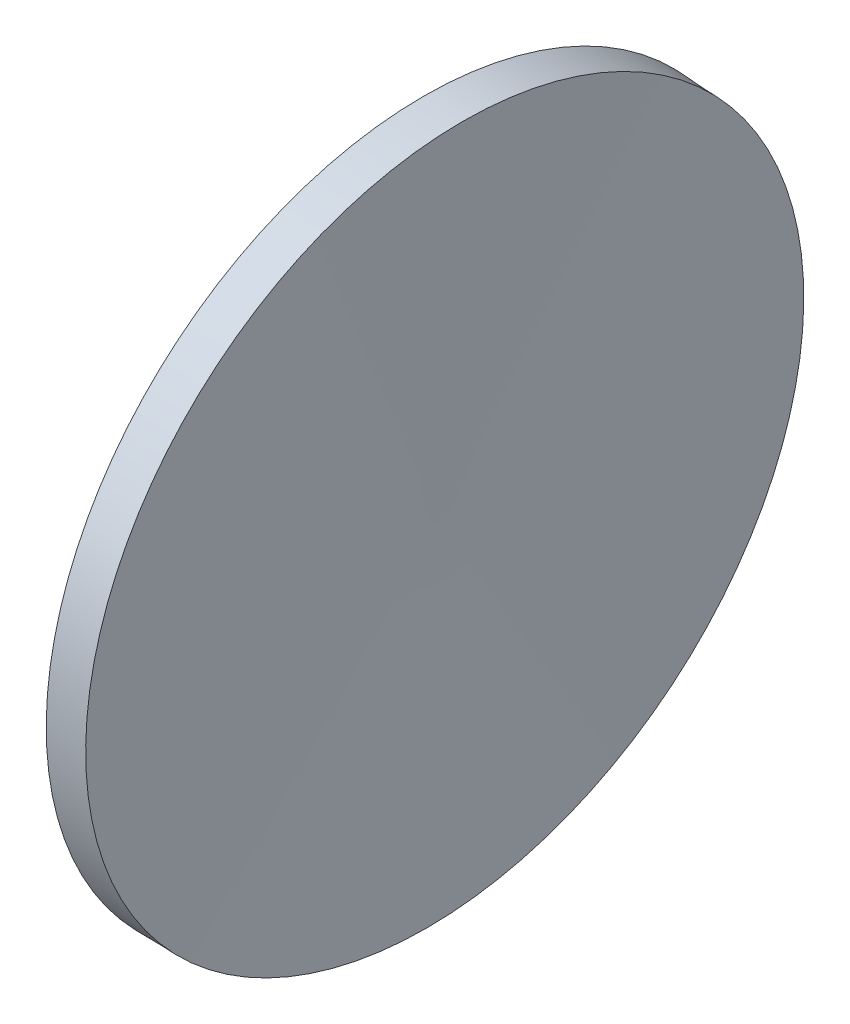
SolidWorks part; units mm, degrees
material "玻璃"
ref_plane "前视基准面" through (0, 0, 0) normal (0, 0, 1) x (1, 0, 0)
ref_plane "上视基准面" through (0, 0, 0) normal (0, 1, 0) x (1, 0, 0)
ref_plane "右视基准面" through (0, 0, 0) normal (1, 0, 0) x (0, 0, -1)
sketch "草图1" plane through (0, 0, 0) normal (0, 0, 1) x (1, 0, 0)
  line L0 (-115.5894, 0.2471) -> (-115.0568, 0.2205)
  line L1 (-115.5894, 0.2471) -> (-115.0568, 0.2205)
  line L2 (-115.0568, 0.2205) -> (-114.9368, 2.069)
  line L3 (-112.0318, 3.89) -> (-112.0765, 3.8998)
  line L4 (-112.0765, 3.8998) -> (-112.0318, 3.89)
  line L5 (-112.0765, 3.8998) -> (-112.0123, 3.8857)
  line L6 (-112.0548, 0.021) -> (-112.052, 0.02)
  line L8 (-115.1374, 2.082) -> (-114.9368, 2.069)
  arc A1 (-115.1374, 2.082) -> (-115.5894, 0.2471) centre (-110.6355, 0) ccw
revolve "旋转1" add sketch "草图1" angle 360 about L0
